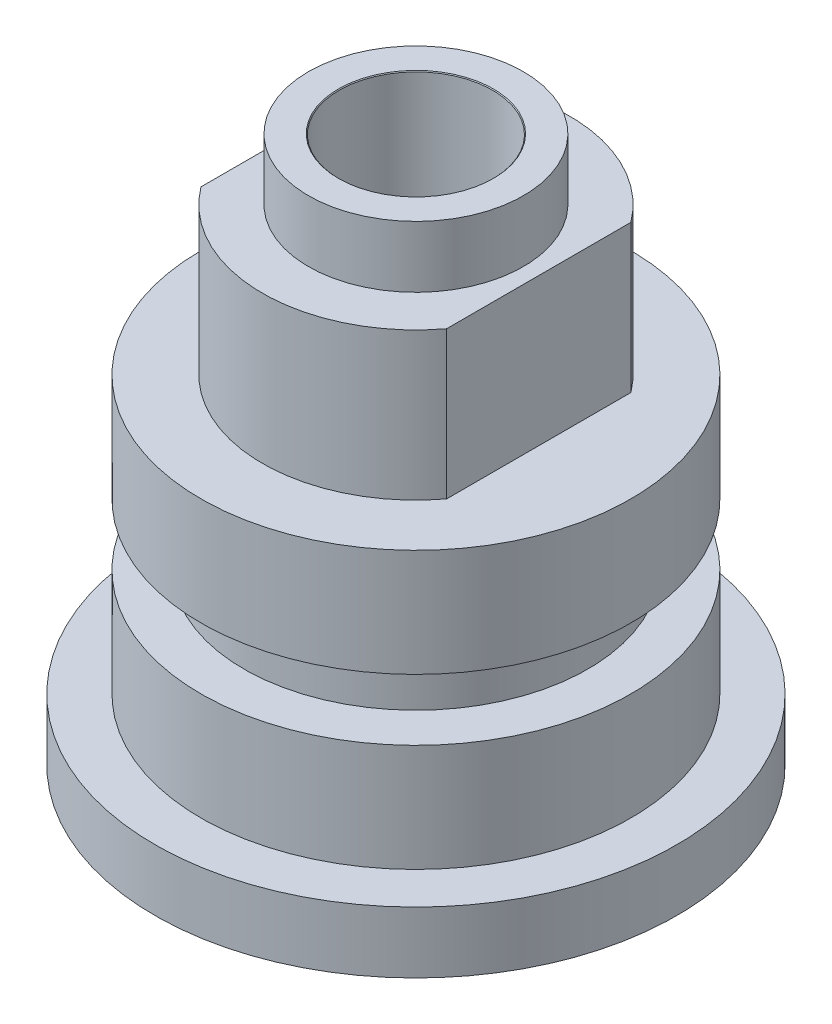
SolidWorks part; units mm, degrees
ref_plane "前视基准面" through (0, 0, 0) normal (0, 0, 1) x (1, 0, 0)
ref_plane "上视基准面" through (0, 0, 0) normal (0, 1, 0) x (1, 0, 0)
ref_plane "右视基准面" through (0, 0, 0) normal (1, 0, 0) x (0, 0, -1)
other "Configuration Table"
sketch "草图1" plane through (0, 0, 0) normal (0, 0, 1) x (1, 0, 0)
  line L0 (0, 0) -> (5, 0)
  line L1 (5, 0) -> (5, 2)
  line L2 (5, 2) -> (8.5, 2)
  line L3 (8.5, 2) -> (8.5, 4)
  line L4 (8.5, 4) -> (7, 4)
  line L5 (7, 4) -> (7, 7.5)
  line L6 (7, 7.5) -> (5.6, 7.5)
  line L7 (5.6, 7.5) -> (5.6, 9.5)
  line L8 (5.6, 9.5) -> (7, 9.5)
  line L9 (7, 9.5) -> (7, 13)
  line L10 (7, 13) -> (5, 13)
  line L11 (5, 13) -> (5, 17.8)
  line L12 (5, 17.8) -> (3.5, 17.8)
  line L13 (3.5, 17.8) -> (3.5, 19.8)
  line L17 (0, 19.8) -> (0, 0) construction
  line L18 (3.5, 19.8) -> (0, 19.8)
  line L19 (0, 0) -> (0, 19.8)
  dimension "D1" = 17
  dimension "D2" = 5
  dimension "D3" = 2
  dimension "D4" = 2
  dimension "D5" = 5.5
  dimension "D6" = 2
  dimension "D7" = 19.8
  dimension "D8" = 11.2
  dimension "D9" = 14
  dimension "D10" = 2
  dimension "D11" = 6.8
  dimension "D12" = 7
  dimension "D13" = 10
revolve "旋转1" add sketch "草图1" angle 360 about L17
sketch "草图3" plane through (0, 17.8, 0) normal (0, 1, 0) x (1, 0, 0)
  line L0 (-4, 3) -> (-4, -3)
  line L1 (4, 3) -> (4, -3)
  line L2 (0, 0) -> (0, 3.5) construction
  circle A0 centre (0, 0) radius 5 construction
  circle A1 centre (0, 0) radius 5 construction
  circle A2 centre (0, 0) radius 3.5 construction
  arc A3 (-4, 3) -> (-4, -3) centre (0, 0) ccw
  arc A4 (4, -3) -> (4, 3) centre (0, 0) ccw
  dimension "D1" = 8
extrude "切除-拉伸1" cut sketch "草图3" against normal up to surface (4.8 mm away) up to face at (-5, 13, 0)
sketch "草图4" plane through (0, 0, 0) normal (0, -1, 0) x (1, 0, 0)
  line L0 (-2.5, 4.3301) -> (-2.5, -4.3301)
  line L1 (2.5, 4.3301) -> (2.5, -4.3301)
  circle A0 centre (0, 0) radius 5 construction
  circle A1 centre (0, 0) radius 5 construction
  arc A2 (-2.5, 4.3301) -> (-2.5, -4.3301) centre (0, 0) ccw
  arc A3 (2.5, -4.3301) -> (2.5, 4.3301) centre (0, 0) ccw
  dimension "D1" = 5
  dimension "D2" = 2.5
extrude "切除-拉伸2" cut sketch "草图4" against normal up to surface (2 mm away) up to face at (-8.5, 2, 0)
hole_wizard "大小mm 暗销孔2" positions "草图5" profile "草图6" hole size "Ø4.0" standard "GB"
sketch "草图5" plane through (0, 0, 0) normal (0, -1, 0) x (-1, 0, 0)
  point P0 (0, 0)
sketch "草图6" plane through (0, 0, 0) normal (1, 0, 0) x (0, 0, -1)
  line L0 (0, 0) -> (0, 2)
  line L1 (0, 2) -> (2, 0.7983)
  line L2 (2, 0.7983) -> (2, 0.025)
  line L3 (2, 0.025) -> (2.025, 0)
  line L5 (2.025, 0) -> (0, 0)
  line L6 (-2, 0.025) -> (-2.025, 0) construction
  line L10 (0, 2) -> (-2, 0.7983) construction
  line L11 (0, -6.35) -> (0, 107.95) construction
  dimension "孔直径" = 4
  dimension "孔深度" = 2
  dimension "近端锥形沉头孔直径" = 4.05
  dimension "近端锥形沉头孔角度" = 90
  dimension "导头角度" = 118
hole_wizard "大小mm 暗销孔1" positions "草图7" profile "草图8" hole size "Ø5.0" standard "GB"
sketch "草图7" plane through (0, 19.8, 0) normal (0, 1, 0) x (1, 0, 0)
  point P0 (0, 0)
sketch "草图8" plane through (0, 19.8, 0) normal (1, 0, 0) x (0, 0, 1)
  line L0 (0, 0) -> (0, 7)
  line L1 (0, 7) -> (2.5, 5.4978)
  line L2 (2.5, 5.4978) -> (2.5, 0.025)
  line L3 (2.5, 0.025) -> (2.525, 0)
  line L5 (2.525, 0) -> (0, 0)
  line L6 (-2.5, 0.025) -> (-2.525, 0) construction
  line L10 (0, 7) -> (-2.5, 5.4978) construction
  line L11 (0, -6.35) -> (0, 107.95) construction
  dimension "孔直径" = 5
  dimension "孔深度" = 7
  dimension "近端锥形沉头孔直径" = 5.05
  dimension "近端锥形沉头孔角度" = 90
  dimension "导头角度" = 118
